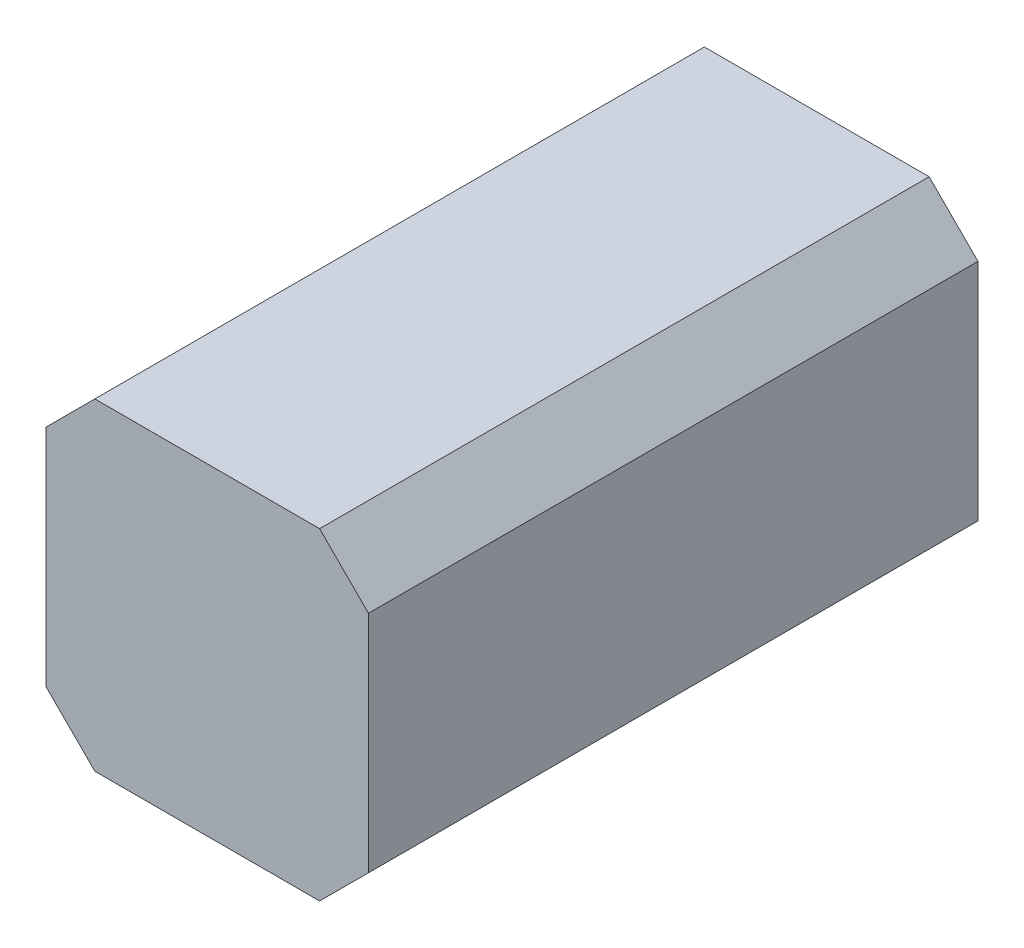
SolidWorks part; units mm, degrees
ref_plane "前视基准面" through (0, 0, 0) normal (0, 0, 1) x (1, 0, 0)
ref_plane "上视基准面" through (0, 0, 0) normal (0, 1, 0) x (1, 0, 0)
ref_plane "右视基准面" through (0, 0, 0) normal (1, 0, 0) x (0, 0, -1)
sketch "草图3" plane through (0, 0, 0) normal (0, 0, 1) x (1, 0, 0)
  line L0 (-77.5, -77.5) -> (77.5, 77.5) construction
  line L1 (-77.5, -77.5) -> (77.5, -77.5)
  line L2 (-77.5, -77.5) -> (-77.5, 77.5)
  line L3 (-77.5, 77.5) -> (77.5, 77.5)
  line L4 (77.5, -77.5) -> (77.5, 77.5)
  line L5 (54.0219, 77.5) -> (77.5, 54.0219)
  line L6 (77.5, -54.0219) -> (54.0219, -77.5)
  line L7 (-77.5, 77.5) -> (77.5, -77.5) construction
  line L8 (-77.5, 54.0219) -> (-54.0219, 77.5)
  line L9 (-54.0219, -77.5) -> (-77.5, -54.0219)
  point P0 (0, 0)
  point P15 (0, 0)
  dimension "D1" = 155
  dimension "D2" = 155
  dimension "D3" = 93
  dimension "D4" = 4
extrude "凸台-拉伸2" add sketch "草图3" along normal blind 293 contours L9 L1 L6 L4 L5 L3 L8 L2
ref_plane "基准面1" through (0, 0, 277) normal (0, 0, -1) x (-1, 0, 0)
scale "缩放比例3" scale about origin uniform scaling yes scale factor 0.4
